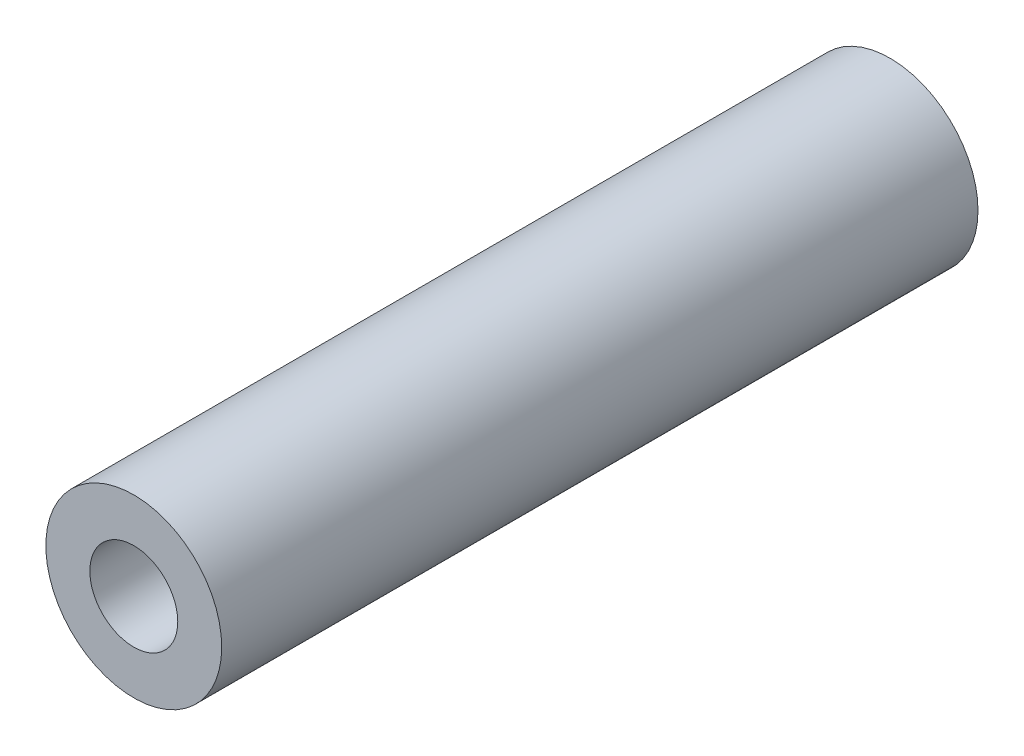
SolidWorks part; units mm, degrees
ref_plane "Front Plane" through (0, 0, 0) normal (0, 0, 1) x (1, 0, 0)
ref_plane "Top Plane" through (0, 0, 0) normal (0, 1, 0) x (1, 0, 0)
ref_plane "Right Plane" through (0, 0, 0) normal (1, 0, 0) x (0, 0, -1)
sketch "Sketch1" plane through (0, 0, 0) normal (0, 0, 1) x (1, 0, 0)
  circle A0 centre (0, 0) radius 5
extrude "Boss-Extrude1" add sketch "Sketch1" along normal blind 43
sketch "Sketch2" plane through (0, 0, 43) normal (0, 0, 1) x (1, 0, 0)
  circle A0 centre (0, 0) radius 2.5
extrude "Cut-Extrude1" cut sketch "Sketch2" against normal blind 40
